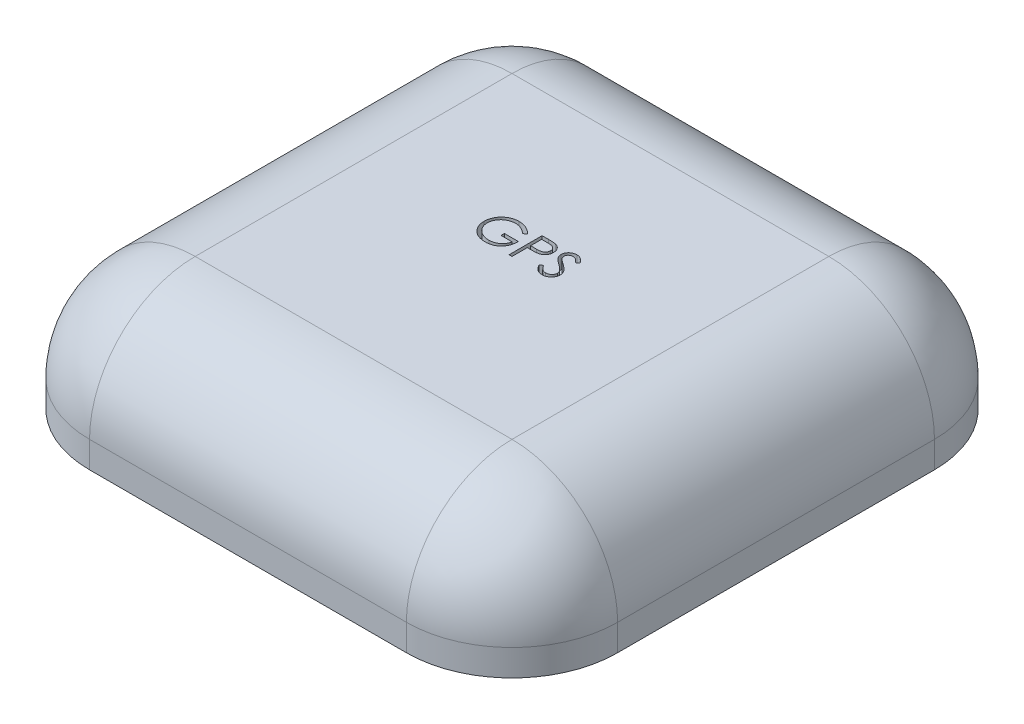
SolidWorks part; units mm, degrees
ref_plane "Front Plane" through (0, 0, 0) normal (0, 0, 1) x (1, 0, 0)
ref_plane "Top Plane" through (0, 0, 0) normal (0, 1, 0) x (1, 0, 0)
ref_plane "Right Plane" through (0, 0, 0) normal (1, 0, 0) x (0, 0, -1)
sketch "Sketch1" plane through (0, 0, 0) normal (0, 1, 0) x (1, 0, 0)
  line L1 (-25.4, -25.4) -> (25.4, -25.4)
  line L2 (-25.4, -25.4) -> (-25.4, 25.4)
  line L3 (-25.4, 25.4) -> (25.4, 25.4)
  line L4 (25.4, -25.4) -> (25.4, 25.4)
  line L5 (-25.4, -25.4) -> (25.4, 25.4) construction
  line L6 (-25.4, 25.4) -> (25.4, -25.4) construction
  point P0 (0, 0)
  dimension "D1" = 50.8
  dimension "D2" = 50.8
extrude "Boss-Extrude1" add sketch "Sketch1" along normal blind 12.7
fillet "Fillet1" radius 10.16 8 edges at (-25.4, 6.35, -25.4) (25.4, 6.35, -25.4) (25.4, 6.35, 25.4) (-25.4, 6.35, 25.4) (-25.4, 12.7, 0) (0, 12.7, -25.4) (25.4, 12.7, 0) (0, 12.7, 25.4)
sketch "Sketch2" plane through (0, 12.7, 0) normal (0, 1, 0) x (1, 0, 0)
  text T0 "GPS"
extrude "Cut-Extrude1" cut sketch "Sketch2" against normal blind 1.27
equation "\"D1@Sketch1\"=\"GPS X@Quad Assemb.sldasm\""
equation "\"D2@Sketch1\"=\"GPS Y@Quad Assemb.sldasm\""
equation "\"D1@Boss-Extrude1\"=\"GPS Z@Quad Assemb.sldasm\""
